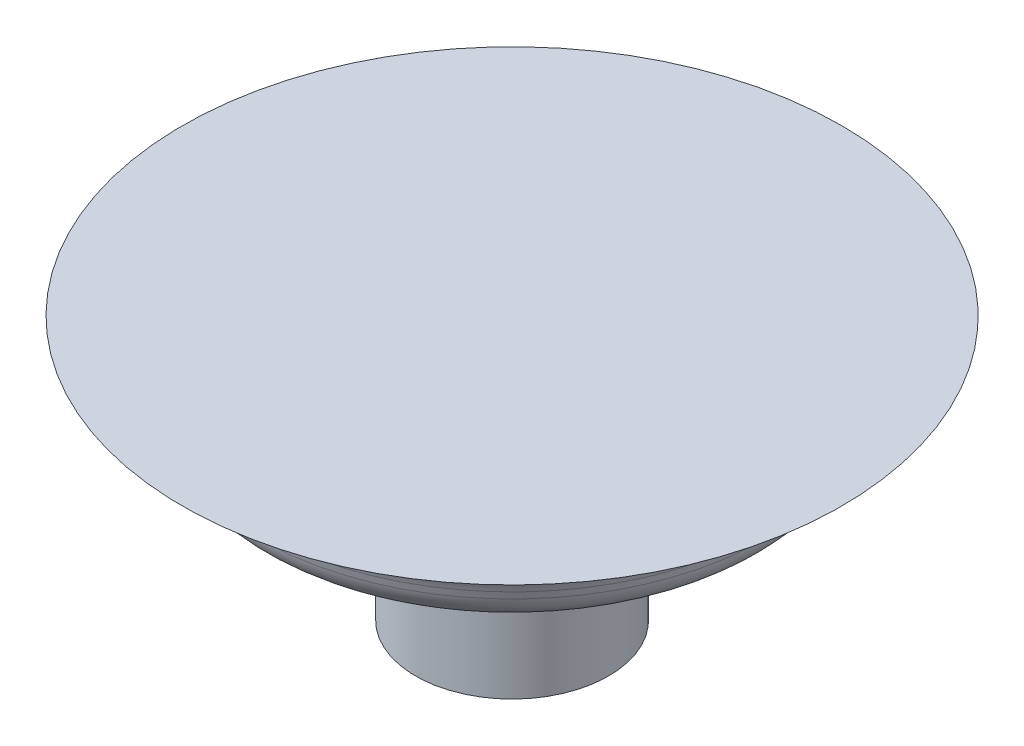
SolidWorks part; units mm, degrees
ref_plane "Спереди" through (0, 0, 0) normal (0, 0, 1) x (1, 0, 0)
ref_plane "Сверху" through (0, 0, 0) normal (0, 1, 0) x (1, 0, 0)
ref_plane "Справа" through (0, 0, 0) normal (1, 0, 0) x (0, 0, -1)
sketch "Эскиз1" plane through (0, 0, 0) normal (0, 0, 1) x (1, 0, 0)
  line L0 (0, 0) -> (0, -2.8)
  line L1 (0, -2.8) -> (1.025, -2.8)
  line L2 (1.025, -2.8) -> (1.025, -1)
  line L3 (1.025, -1) -> (2.3141, -1)
  line L4 (2.7032, -0.6926) -> (2.7217, -0.6148)
  line L5 (0, 0) -> (3.5, 0)
  line L8 (0, 0) -> (0, 3.2822) construction
  arc A0 (3.5, 0) -> (2.7217, -0.6148) centre (3.5, -0.8) ccw
  arc A1 (2.3141, -1) -> (2.7032, -0.6926) centre (2.3141, -0.6) ccw
  point P14 (3.5, 0)
  dimension "D2" = 0.8
  dimension "D1" = 1.6
  dimension "D3" = 7
  dimension "D4" = 1
  dimension "D5" = 4.6282
  dimension "D6" = 2.05
  dimension "D7" = 1.8
revolve "Повернуть1" add sketch "Эскиз1" angle 360 about L8
sketch "Эскиз ориентации" plane through (0, 0, 0) normal (0, 1, 0) x (1, 0, 0)
  circle A0 centre (0, 0) radius 3.5 construction
  circle A1 centre (0, 0) radius 3.5
  point P3 (0, 0)
other "Инструмент формы1"
